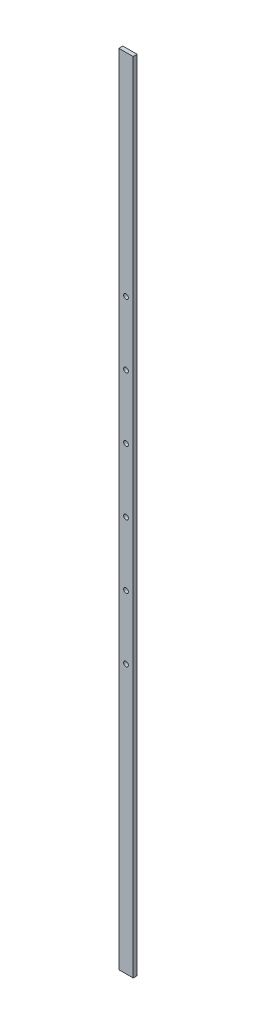
SolidWorks part; units mm, degrees
material "ASTM A36 Steel"
ref_plane "Front Plane" through (0, 0, 0) normal (0, 0, 1) x (1, 0, 0)
ref_plane "Top Plane" through (0, 0, 0) normal (0, 1, 0) x (1, 0, 0)
ref_plane "Right Plane" through (0, 0, 0) normal (1, 0, 0) x (0, 0, -1)
sketch "Sketch1" plane through (0, 0, 0) normal (0, 0, 1) x (1, 0, 0)
  line L1 (-9, -501.5) -> (9, -501.5)
  line L2 (-9, -501.5) -> (-9, 501.5)
  line L3 (-9, 501.5) -> (9, 501.5)
  line L4 (9, -501.5) -> (9, 501.5)
  line L5 (-9, -501.5) -> (9, 501.5) construction
  line L6 (-9, 501.5) -> (9, -501.5) construction
  point P0 (0, 0)
  dimension "D1" = 1003
  dimension "D2" = 18
extrude "Boss-Extrude1" add sketch "Sketch1" along normal blind 5
sketch "Sketch2" plane through (0, 0, 5) normal (0, 0, 1) x (1, 0, 0)
  line L1 (9, 501.5) -> (-9, 501.5) construction
  circle A0 centre (0, 235.85) radius 3
  dimension "D2" = 6
  dimension "D1" = 265.65
extrude "Cut-Extrude1" cut sketch "Sketch2" against normal blind 5
pattern_linear "LPattern1" count 6 spacing 80 along (0, -1, 0) of "Cut-Extrude1"
